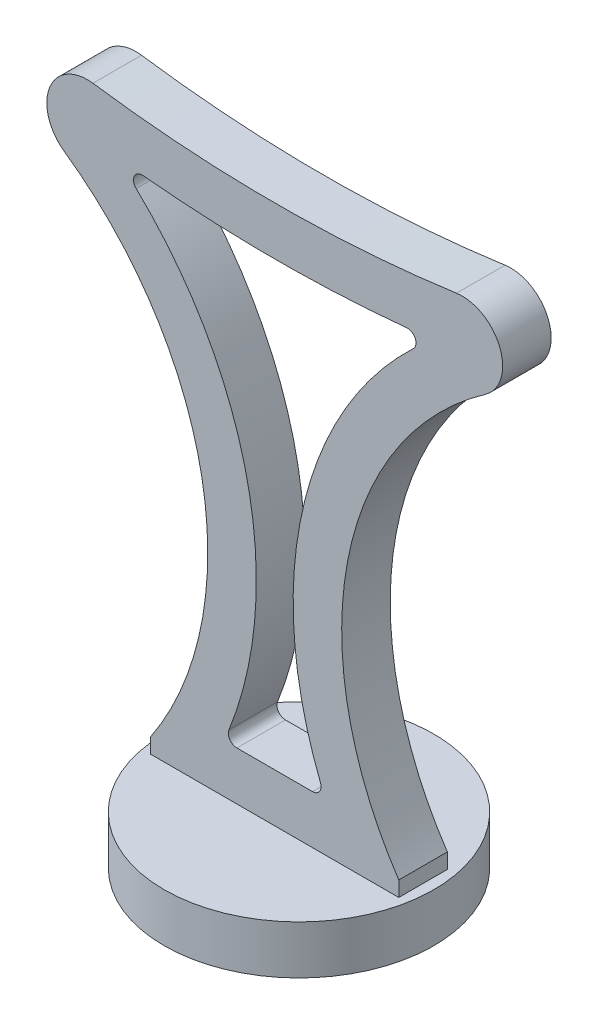
SolidWorks part; units mm, degrees
material "Pine"
ref_plane "Front Plane" through (0, 0, 0) normal (0, 0, 1) x (1, 0, 0)
ref_plane "Top Plane" through (0, 0, 0) normal (0, 1, 0) x (1, 0, 0)
ref_plane "Right Plane" through (0, 0, 0) normal (1, 0, 0) x (0, 0, -1)
sketch "Sketch2" plane through (0, 0, 0) normal (0, 1, 0) x (1, 0, 0)
  circle A0 centre (0, 0) radius 50
  dimension "D1" = 100
extrude "Boss-Extrude1" add sketch "Sketch2" along normal blind 18
sketch "Sketch3" plane through (0, 0, 0) normal (0, 0, 1) x (1, 0, 0)
  line L0 (50, 18) -> (-50, 18) construction
  line L1 (-15, 14.825) -> (-15, 0)
  line L2 (46, 18) -> (18.175, 18)
  line L3 (0, 0) -> (0, 171.1978) construction
  line L4 (-50, 0) -> (50, 0) construction
  line L5 (-46, 23.625) -> (-46, 18)
  line L6 (-15, 0) -> (15, 0)
  line L7 (15, 0) -> (15, 14.825)
  line L8 (-18.175, 18) -> (-46, 18)
  line L9 (46, 23.625) -> (46, 18)
  arc A0 (-84.4804, 207.1886) -> (84.4804, 207.1886) centre (0, 700) ccw construction
  arc A1 (-67.399, 222.7355) -> (67.399, 222.7355) centre (0, 700) ccw
  arc A2 (-46, 23.625) -> (-78.1037, 195.5981) centre (-149.8308, 93.2251) ccw
  arc A3 (46, 23.625) -> (78.1037, 195.5981) centre (149.8308, 93.2251) cw
  arc A6 (15, 14.825) -> (18.175, 18) centre (18.175, 14.825) cw
  circle A7 centre (0, 700) radius 500 construction
  circle A8 centre (0, 700) radius 482 construction
  arc A9 (-15, 14.825) -> (-18.175, 18) centre (-18.175, 14.825) ccw
  arc A10 (-67.399, 222.7355) -> (-78.1037, 195.5981) centre (-69.4965, 207.8829) ccw
  arc A11 (67.399, 222.7355) -> (78.1037, 195.5981) centre (69.4965, 207.8829) cw
  point P1 (126.2322, 388.5931)
  point P7 (0, 218)
  point P21 (143.4457, 393.8558)
  point P31 (-15, 18)
  dimension "D1" = 1000
  dimension "D4" = 250
  dimension "D7" = 3.175
  dimension "D8" = 30
  dimension "D3" = 200
  dimension "D5" = 30
  dimension "D6" = 15
  dimension "D9" = 46
  dimension "D10" = 46
  dimension "D2" = 18
extrude "Boss-Extrude2" add sketch "Sketch3" along normal mid plane 18 separate body
sketch "Sketch4" plane through (0, 0, 9) normal (0, 0, 1) x (1, 0, 0)
  line L10 (-18.7801, 36) -> (-18.175, 36)
  line L11 (18.175, 36) -> (18.7801, 36)
  line L12 (-14.0158, 36) -> (14.0158, 36)
  arc A7 (16.9657, 40.349) -> (14.0158, 36) centre (14.0158, 39.175) cw
  arc A8 (-16.9657, 40.349) -> (-14.0158, 36) centre (-14.0158, 39.175) ccw
  arc A9 (51.3736, 196.9323) -> (48.8772, 202.3947) centre (49.1876, 199.2349) ccw
  arc A10 (-48.8772, 202.3947) -> (-51.3736, 196.9323) centre (-49.1876, 199.2349) ccw
  arc A14 (58.745, 203.463) -> (18.7801, 36) centre (149.8308, 93.2251) ccw
  arc A15 (-58.745, 203.463) -> (58.745, 203.463) centre (0, 700) ccw
  arc A16 (-18.7801, 36) -> (-58.745, 203.463) centre (-149.8308, 93.2251) ccw
  arc A17 (0, 25.6901) -> (-18.175, 36) centre (-18.175, 14.825) ccw
  arc A18 (18.175, 36) -> (0, 25.6901) centre (18.175, 14.825) ccw
  arc A19 (51.3736, 196.9323) -> (16.9657, 40.349) centre (149.8308, 93.2251) ccw
  arc A20 (-48.8772, 202.3947) -> (48.8772, 202.3947) centre (0, 700) ccw
  arc A21 (-16.9657, 40.349) -> (-51.3736, 196.9323) centre (-149.8308, 93.2251) ccw
  dimension "D2" = 3.175
  dimension "D1" = 18
extrude "Cut-Extrude1" cut sketch "Sketch4" against normal through all
sketch "Sketch5" plane through (0, 18, 0) normal (0, 1, 0) x (1, 0, 0)
  line L0 (-15, 9) -> (-15, -9)
  line L1 (15, 9) -> (15, -9)
  line L4 (15, 9) -> (-15, 9)
  line L5 (15, -9) -> (15, 9)
  line L6 (-15, -9) -> (15, -9)
  line L7 (-15, 9) -> (-15, -9)
  line L8 (15, 9) -> (-15, 9)
  line L10 (-15, -9) -> (15, -9)
  dimension "D1" = 0
extrude "Cut-Extrude2" cut sketch "Sketch5" against normal through all both and the other way through all
chamfer "Chamfer1" distance 4 angle 45 2 edges at (15, 18, 0) (-15, 18, 0)
sketch "Sketch6" plane through (0, 0, 0) normal (0, -1, 0) x (1, 0, 0)
  line L0 (-15, -9) -> (-15, 9) construction
  line L1 (15, 9) -> (15, -9) construction
  line L2 (15, -9) -> (-15, -9) construction
  circle A0 centre (-15, 7.4125) radius 1.5875
  circle A1 centre (-15, -7.4125) radius 1.5875
  circle A2 centre (15, 7.4125) radius 1.5875
  circle A3 centre (15, -7.4125) radius 1.5875
  dimension "D1" = 3.175
extrude "Cut-Extrude3" cut sketch "Sketch6" against normal blind 18
delete or keep bodies "Body-Delete/Keep 1" [suppressed] type keep bodies bodies 105
delete or keep bodies "Body-Delete/Keep 2" [suppressed] type delete bodies bodies 105
